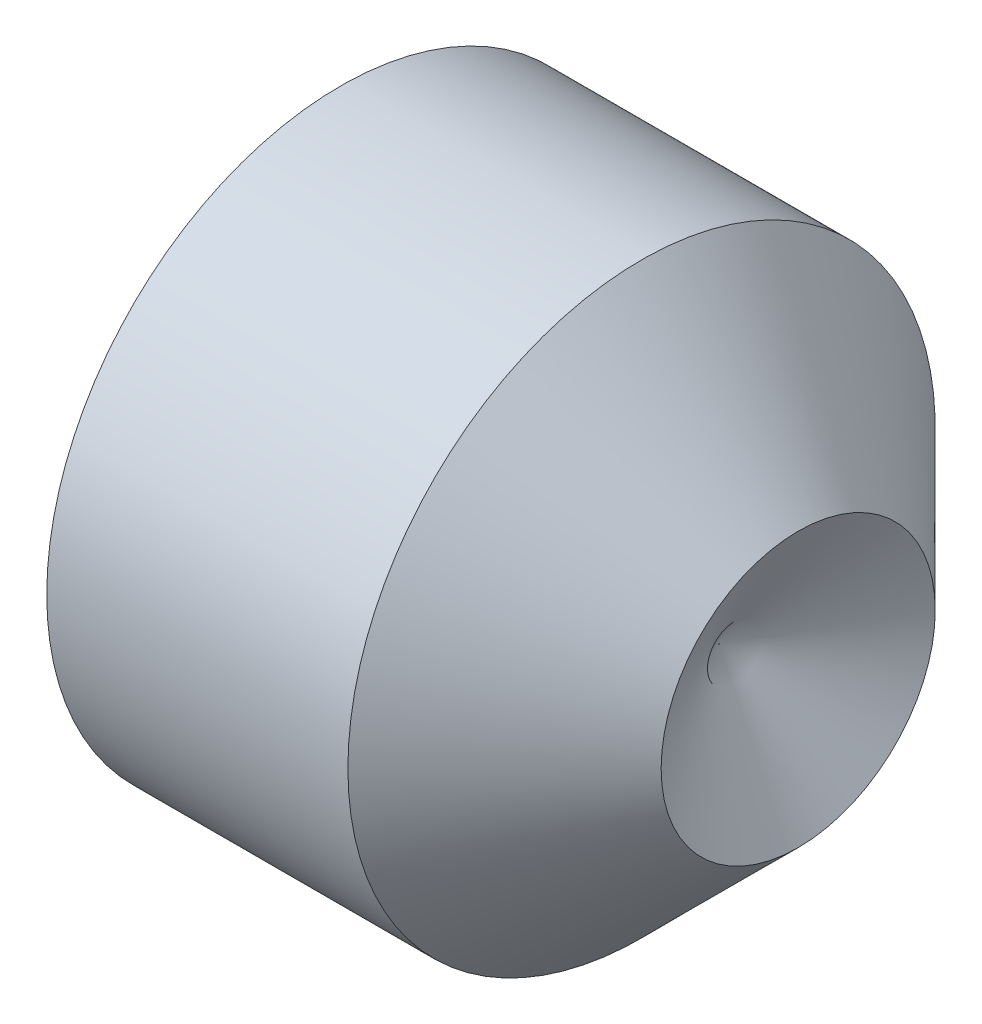
SolidWorks part; units mm, degrees
revolve "BaseBody" add sketch "BodySke" angle 360 about L5
sketch "BodySke" plane through (0, 0, 0) normal (0, 0, 1) x (1, 0, 0)
  line L0 (0, 0) -> (0, 1.2195)
  line L1 (0, 1.2195) -> (0.1619, 1.5)
  line L2 (0.1619, 1.5) -> (1.7, 1.5)
  line L3 (1.7, 1.5) -> (2.5, 0.7)
  line L4 (2.0959, 0) -> (0, 0)
  line L5 (-12.7, 0) -> (88.9, 0) construction
  line L6 (2.0959, 0) -> (2.5, 0.7)
  line L7 (2.5, 0.7) -> (2.5, 10.225) construction
  line L8 (0, -1.2195) -> (0.1619, -1.5) construction
  line L9 (2.0959, 0) -> (2.5, -0.7) construction
  line L10 (1.7, -1.5) -> (2.5, -0.7) construction
  line L11 (0.25, 15.875) -> (0.25, -3.175) construction
  dimension "Diameter" = 3
  dimension "Drive_ch_ang" = 60
  dimension "Minor_dia" = 2.439
  dimension "Cup_ang" = 120
  dimension "Cup_dia" = 1.4
  dimension "Length" = 2.5
  dimension "Cup_nose_ang" = 45
  dimension "Advance" = 0.5
cosmetic thread "ThreadCosmetic" [suppressed] parameters "Thread_minor"=2.439
ref_plane "Plane1" through (0, 0, 0) normal (0, 0, 1) x (1, 0, 0)
ref_plane "Plane2" through (0, 0, 0) normal (0, 1, 0) x (1, 0, 0)
ref_plane "Plane3" through (0, 0, 0) normal (1, 0, 0) x (0, 0, -1)
other "Configuration Table"
sketch "Sketch2" plane through (0, 0, 0) normal (-1, 0, 0) x (0, 0, 1)
  line L0 (0.433, 0.75) -> (-0.433, 0.75)
  line L1 (-0.433, 0.75) -> (-0.866, 0)
  line L2 (0.433, 0.75) -> (0.866, 0)
  line L3 (0.433, -0.75) -> (0.866, 0)
  line L4 (0.433, -0.75) -> (-0.433, -0.75)
  line L5 (-0.433, -0.75) -> (-0.866, 0)
  dimension "Hex_size" = 1.5
  dimension "D2" = 0.75
  dimension "D3" = 0.75
extrude "Hex" cut sketch "Sketch2" against normal blind 1.2
sketch "ThdSchSke" plane through (0, 0, 0) normal (0, 0, 1) x (1, 0, 0)
  line L0 (0.1619, -1.2195) -> (-0.0345, -1.5)
  line L1 (0.1619, -1.2195) -> (0.3584, -1.5)
  line L2 (0.3584, -1.5) -> (0.3584, -1.875)
  line L3 (-3.175, 0) -> (5.1513, 0) construction
  line L4 (0.1619, 1.5) -> (0.1619, -1.5) construction
  line L5 (0.3584, -1.875) -> (-0.0345, -1.875)
  line L6 (-0.0345, -1.875) -> (-0.0345, -1.5)
  dimension "Thread_minor" = 2.439
  dimension "Diameter" = 3
revolve "ThreadSchematic" [suppressed] cut sketch "ThdSchSke" angle 360 about L3
pattern_linear "ThdSchPat" [suppressed]
equation "\"D2@Sketch2\" = \"Hex_size@Sketch2\" / 2"
equation "\"D3@Sketch2\" = \"Hex_size@Sketch2\" / 2"
equation "\"Thread_minor@ThreadCosmetic\" = \"Minor_dia@BodySke\""
equation "\"Thread_minor@ThdSchSke\" = \"Thread_minor@ThreadCosmetic\""
equation "\"Diameter@ThdSchSke\" = \"Diameter@BodySke\""
equation "\"Overcut@ThdSchSke\" = \"Diameter@BodySke\" * 1.25"
equation "\"Num_threads@ThdSchPat\" = int( (\"Length@BodySke\" - ( ( ( \"Diameter@BodySke\" - \"Minor_dia@BodySke\" ) * 0.5 ) / tan( \"Drive_ch_ang@BodySke\" * 0.017453292 ) ) - ( ( ( \"Diameter@BodySke\" - \"Cup_dia@BodySke\" ) * 0.5 ) * tan( \"Cup_nose_ang@BodySke\" * 0.017453292 ) ) ) / \"Advance@BodySke\" + 0.999 )  + 1"
equation "\"Advance@ThdSchPat\" = (\"Length@BodySke\" - ( ( ( \"Diameter@BodySke\" - \"Minor_dia@BodySke\" ) * 0.5 ) / tan( \"Drive_ch_ang@BodySke\" * 0.017453292 ) ) - ( ( ( \"Diameter@BodySke\" - \"Cup_dia@BodySke\" ) * 0.5 ) * tan( \"Cup_nose_ang@BodySke\" * 0.017453292 ) ) ) /  (\"Num_threads@ThdSchPat\" - 1) 'relax it"
equation "' \"Num_threads@ThdSchPat\" = \"Num_threads@ThdSchPat\" - sgn( \"Num_threads@ThdSchPat\" - 1) '---chamfered tips only---"
